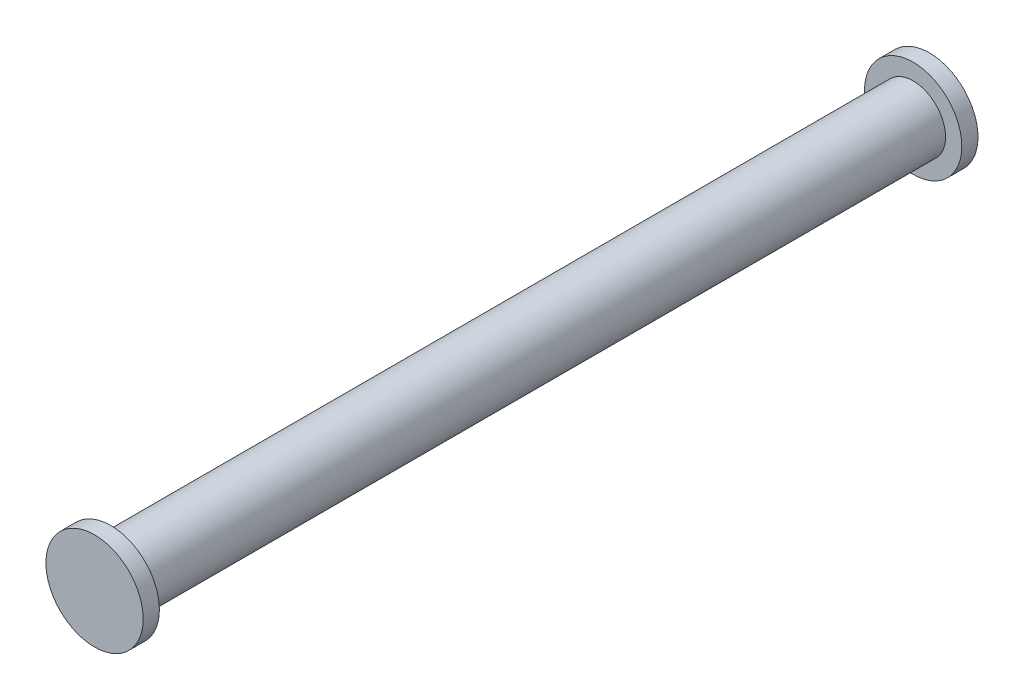
SolidWorks part; units mm, degrees
ref_plane "Front" through (0, 0, 0) normal (0, 0, 1) x (1, 0, 0)
ref_plane "Top" through (0, 0, 0) normal (0, 1, 0) x (1, 0, 0)
ref_plane "Right" through (0, 0, 0) normal (1, 0, 0) x (0, 0, -1)
sketch "草图1" plane through (0, 0, 0) normal (0, 0, 1) x (1, 0, 0)
  circle A0 centre (0, 0) radius 6
  dimension "D1" = 12
extrude "凸台-拉伸1" add sketch "草图1" along normal blind 2
sketch "草图2" plane through (0, 0, 2) normal (0, 0, 1) x (1, 0, 0)
  circle A0 centre (0, 0) radius 4
  dimension "D1" = 8
extrude "凸台-拉伸2" add sketch "草图2" along normal blind 99
sketch "草图3" plane through (0, 0, 101) normal (0, 0, 1) x (1, 0, 0)
  circle A0 centre (0, 0) radius 6
  dimension "D1" = 12
extrude "凸台-拉伸3" add sketch "草图3" along normal blind 2
